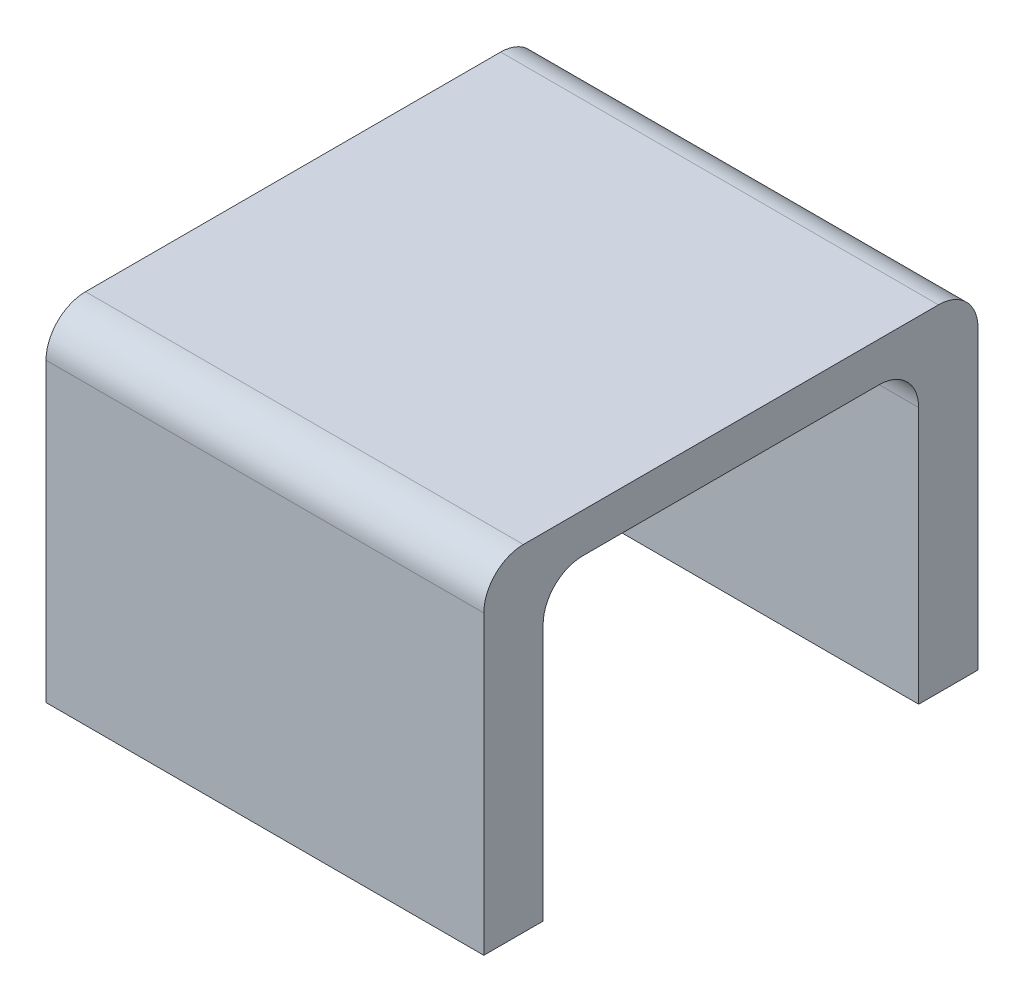
SolidWorks part; units mm, degrees
ref_plane "Plan de face" through (0, 0, 0) normal (0, 0, 1) x (1, 0, 0)
ref_plane "Plan de dessus" through (0, 0, 0) normal (0, 1, 0) x (1, 0, 0)
ref_plane "Plan de droite" through (0, 0, 0) normal (1, 0, 0) x (0, 0, -1)
sketch "Esquisse2" plane through (0, 0, 0) normal (0, 1, 0) x (1, 0, 0)
  line L1 (6.1663, 12.8401) -> (28.3163, 12.8401)
  line L2 (6.1663, 12.8401) -> (6.1663, -12.1599)
  line L3 (6.1663, -12.1599) -> (28.3163, -12.1599)
  line L4 (28.3163, 12.8401) -> (28.3163, -12.1599)
  dimension "D1" = 25
  dimension "D2" = 22.15
extrude "Boss.-Extru.1" add sketch "Esquisse2" along normal blind 17
sketch "Esquisse3" plane through (0, 0, 0) normal (0, -1, 0) x (1, 0, 0)
  line L0 (6.1663, -12.8401) -> (6.1663, 12.1599) construction
  line L1 (6.1663, 9.1599) -> (28.3163, 9.1599)
  line L2 (6.1663, 9.1599) -> (6.1663, -9.8401)
  line L3 (6.1663, -9.8401) -> (28.3163, -9.8401)
  line L4 (28.3163, 9.1599) -> (28.3163, -9.8401)
  line L5 (28.3163, 12.1599) -> (28.3163, -12.8401) construction
  line L6 (6.1663, 12.1599) -> (28.3163, 12.1599) construction
  line L7 (28.3163, -12.8401) -> (6.1663, -12.8401) construction
  dimension "D1" = 3
  dimension "D2" = 3
extrude "Enlèv. mat.-Extru.1" cut sketch "Esquisse3" against normal blind 15
fillet "Congé1" radius 2 2 edges at (17.2413, 15, -9.8401) (17.2413, 15, 9.1599)
fillet "Congé2" radius 2 2 edges at (17.2413, 17, -12.8401) (17.2413, 17, 12.1599)
